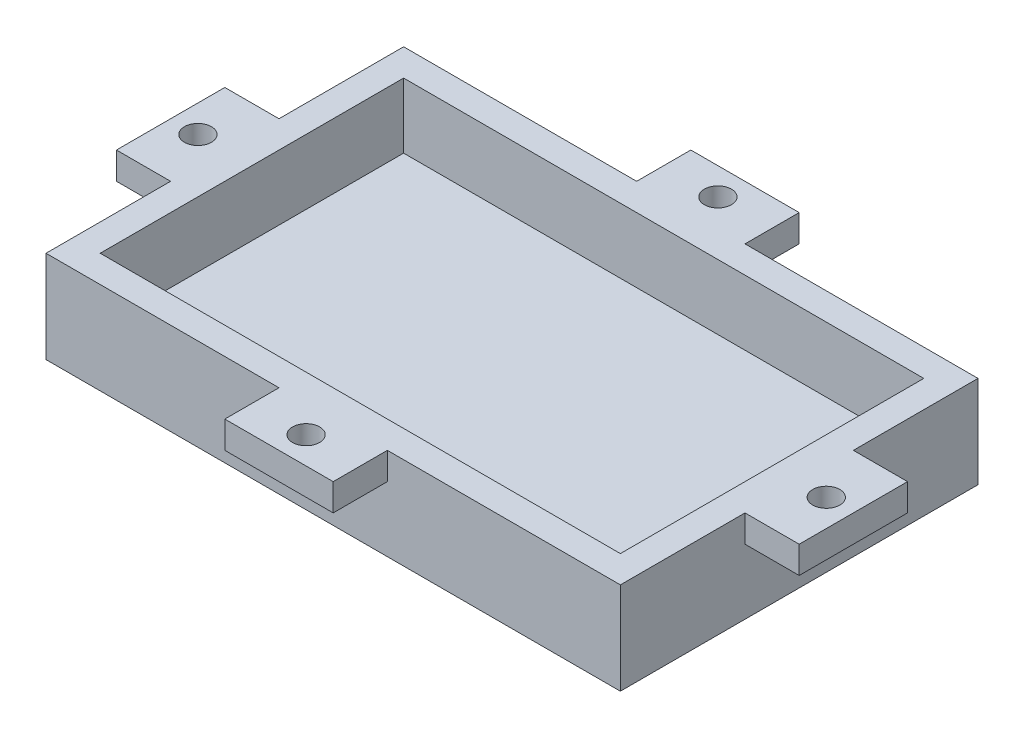
SolidWorks part; units mm, degrees
ref_plane "Front Plane" through (0, 0, 0) normal (0, 0, 1) x (1, 0, 0)
ref_plane "Top Plane" through (0, 0, 0) normal (0, 1, 0) x (1, 0, 0)
ref_plane "Right Plane" through (0, 0, 0) normal (1, 0, 0) x (0, 0, -1)
sketch "Sketch1" plane through (0, 0, 0) normal (0, 1, 0) x (1, 0, 0)
  line L1 (-30.48, 17.78) -> (30.48, 17.78)
  line L2 (-30.48, 17.78) -> (-30.48, -17.78)
  line L3 (-30.48, -17.78) -> (30.48, -17.78)
  line L4 (30.48, 17.78) -> (30.48, -17.78)
  line L5 (-30.48, 17.78) -> (30.48, -17.78) construction
  line L6 (-30.48, -17.78) -> (30.48, 17.78) construction
  line L7 (-33.655, 20.955) -> (33.655, 20.955)
  line L8 (-33.655, 20.955) -> (-33.655, -20.955)
  line L9 (-33.655, -20.955) -> (33.655, -20.955)
  line L10 (33.655, 20.955) -> (33.655, -20.955)
  line L11 (-33.655, 20.955) -> (33.655, -20.955) construction
  line L12 (-33.655, -20.955) -> (33.655, 20.955) construction
  point P0 (0, 0)
  point P6 (0, 0)
  dimension "D1" = 60.96
  dimension "D2" = 35.56
  dimension "D3" = 67.31
  dimension "D4" = 41.91
extrude "Boss-Extrude5" add sketch "Sketch1" along normal blind 3.175 contours L8 L7 L10 L9
sketch "Sketch2" plane through (0, 3.175, 0) normal (0, 1, 0) x (1, 0, 0)
  line L1 (-30.48, 17.78) -> (30.48, 17.78)
  line L2 (-30.48, 17.78) -> (-30.48, -17.78)
  line L3 (-30.48, -17.78) -> (30.48, -17.78)
  line L4 (30.48, 17.78) -> (30.48, -17.78)
  line L5 (-30.48, 17.78) -> (30.48, -17.78) construction
  line L6 (-30.48, -17.78) -> (30.48, 17.78) construction
  line L7 (-33.655, 20.955) -> (33.655, 20.955)
  line L8 (-33.655, 20.955) -> (-33.655, -20.955)
  line L9 (-33.655, -20.955) -> (33.655, -20.955)
  line L10 (33.655, 20.955) -> (33.655, -20.955)
  line L11 (-33.655, 20.955) -> (33.655, -20.955) construction
  line L12 (-33.655, -20.955) -> (33.655, 20.955) construction
  point P0 (0, 0)
  point P6 (0, 0)
  dimension "D1" = 60.96
  dimension "D2" = 35.56
extrude "Boss-Extrude6" add sketch "Sketch2" along normal blind 7.62
sketch "Sketch4" plane through (0, 10.795, 0) normal (0, 1, 0) x (1, 0, 0)
  line L0 (33.655, 0) -> (40.005, 0)
  line L1 (33.655, -20.955) -> (33.655, 20.955) construction
  line L2 (0, -20.955) -> (0, -27.305)
  line L3 (-33.655, -20.955) -> (33.655, -20.955) construction
  line L4 (0, 20.955) -> (0, 27.305)
  line L5 (33.655, 20.955) -> (-33.655, 20.955) construction
  line L6 (-33.655, 0) -> (-40.005, 0)
  line L7 (-33.655, 20.955) -> (-33.655, -20.955) construction
  line L9 (-6.35, -20.955) -> (6.35, -20.955)
  line L10 (-6.35, -20.955) -> (-6.35, -27.305)
  line L11 (-6.35, -27.305) -> (6.35, -27.305)
  line L12 (6.35, -20.955) -> (6.35, -27.305)
  line L13 (-6.35, -20.955) -> (6.35, -27.305) construction
  line L14 (-6.35, -27.305) -> (6.35, -20.955) construction
  line L15 (-6.35, 27.305) -> (6.35, 27.305)
  line L16 (-6.35, 27.305) -> (-6.35, 20.955)
  line L17 (-6.35, 20.955) -> (6.35, 20.955)
  line L18 (6.35, 27.305) -> (6.35, 20.955)
  line L19 (-6.35, 27.305) -> (6.35, 20.955) construction
  line L20 (-6.35, 20.955) -> (6.35, 27.305) construction
  line L21 (33.655, 6.35) -> (40.005, 6.35)
  line L22 (33.655, 6.35) -> (33.655, -6.35)
  line L23 (33.655, -6.35) -> (40.005, -6.35)
  line L24 (40.005, 6.35) -> (40.005, -6.35)
  line L25 (33.655, 6.35) -> (40.005, -6.35) construction
  line L26 (33.655, -6.35) -> (40.005, 6.35) construction
  line L27 (-40.005, 6.35) -> (-33.655, 6.35)
  line L28 (-40.005, 6.35) -> (-40.005, -6.35)
  line L29 (-40.005, -6.35) -> (-33.655, -6.35)
  line L30 (-33.655, 6.35) -> (-33.655, -6.35)
  line L31 (-40.005, 6.35) -> (-33.655, -6.35) construction
  line L32 (-40.005, -6.35) -> (-33.655, 6.35) construction
  point P17 (0, -24.13)
  point P22 (0, 24.13)
  point P27 (36.83, 0)
  point P32 (-36.83, 0)
  dimension "D1" = 6.35
  dimension "D2" = 6.35
  dimension "D3" = 6.35
  dimension "D4" = 6.35
  dimension "D5" = 12.7
  dimension "D6" = 12.7
  dimension "D7" = 12.7
  dimension "D8" = 12.7
extrude "Boss-Extrude8" add sketch "Sketch4" against normal blind 3.175 contours L29 L30 L27 L28 | L18 L17 L16 L15 | L23 L24 L21 L22 | L12 L11 L10 L9
sketch "Sketch6" plane through (0, 10.795, 0) normal (0, 1, 0) x (1, 0, 0)
  line L0 (-40.005, 0) -> (-33.6078, 0)
  line L1 (-40.005, 6.35) -> (-40.005, -6.35) construction
  line L2 (-33.6078, 0) -> (-33.655, 6.35)
  line L3 (-33.655, 6.35) -> (-33.655, -6.35)
  line L4 (-40.005, -6.35) -> (-33.655, -6.35) construction
  line L5 (-6.35, 20.955) -> (6.35, 20.955)
  line L6 (0, 20.955) -> (0, 27.305)
  line L7 (-6.35, 27.305) -> (6.35, 27.305) construction
  line L8 (33.655, 6.35) -> (33.655, -6.35)
  line L9 (40.005, 6.35) -> (40.005, -6.35) construction
  line L10 (40.005, 0) -> (33.655, 0)
  line L11 (-6.35, -20.955) -> (6.35, -20.955)
  line L12 (0, -20.955) -> (0, -27.305)
  line L13 (-6.35, -27.305) -> (6.35, -27.305) construction
  circle A0 centre (-36.8064, 0) radius 1.5875
  circle A1 centre (36.83, 0) radius 1.5875
  circle A2 centre (0, -24.13) radius 1.5875
  circle A3 centre (0, 24.13) radius 1.5875
extrude "Cut-Extrude1" cut sketch "Sketch6" against normal through all contours L6 A3 | A0 | A1 | A2
